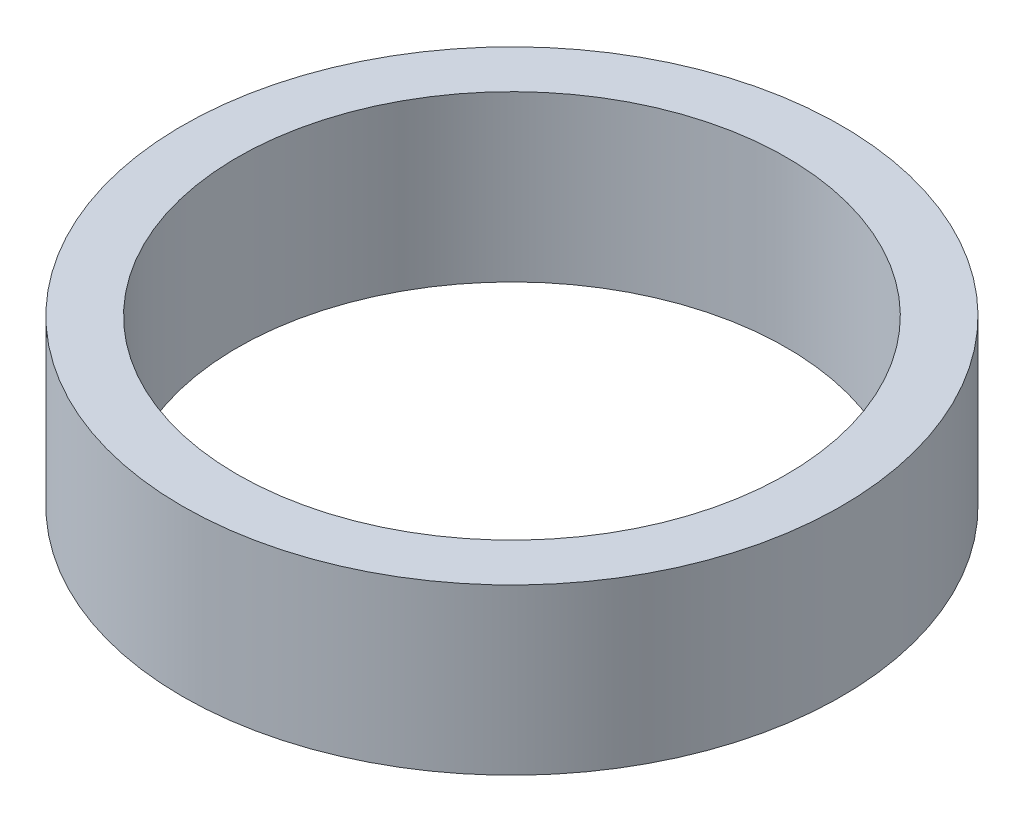
SolidWorks part; units mm, degrees
ref_plane "Front Plane" through (0, 0, 0) normal (0, 0, 1) x (1, 0, 0)
ref_plane "Top Plane" through (0, 0, 0) normal (0, 1, 0) x (1, 0, 0)
ref_plane "Right Plane" through (0, 0, 0) normal (1, 0, 0) x (0, 0, -1)
sketch "Sketch1" plane through (0, 0, 0) normal (0, 1, 0) x (1, 0, 0)
  line L0 (0, 0) -> (0, 6) construction
  line L1 (0, -6) -> (0, 6)
  circle A0 centre (0, 0) radius 6
  point P7 (0, 0)
  dimension "D1" = 6
extrude "Boss-Extrude2" add sketch "Sketch1" along normal blind 3 contours A0
sketch "Sketch3" plane through (0, 3, 0) normal (0, 1, 0) x (1, 0, 0)
  line L0 (0, 0) -> (4, 0) construction
  circle A0 centre (0, 0) radius 5
  dimension "D1" = 4
extrude "Cut-Extrude1" cut sketch "Sketch3" against normal blind 20
